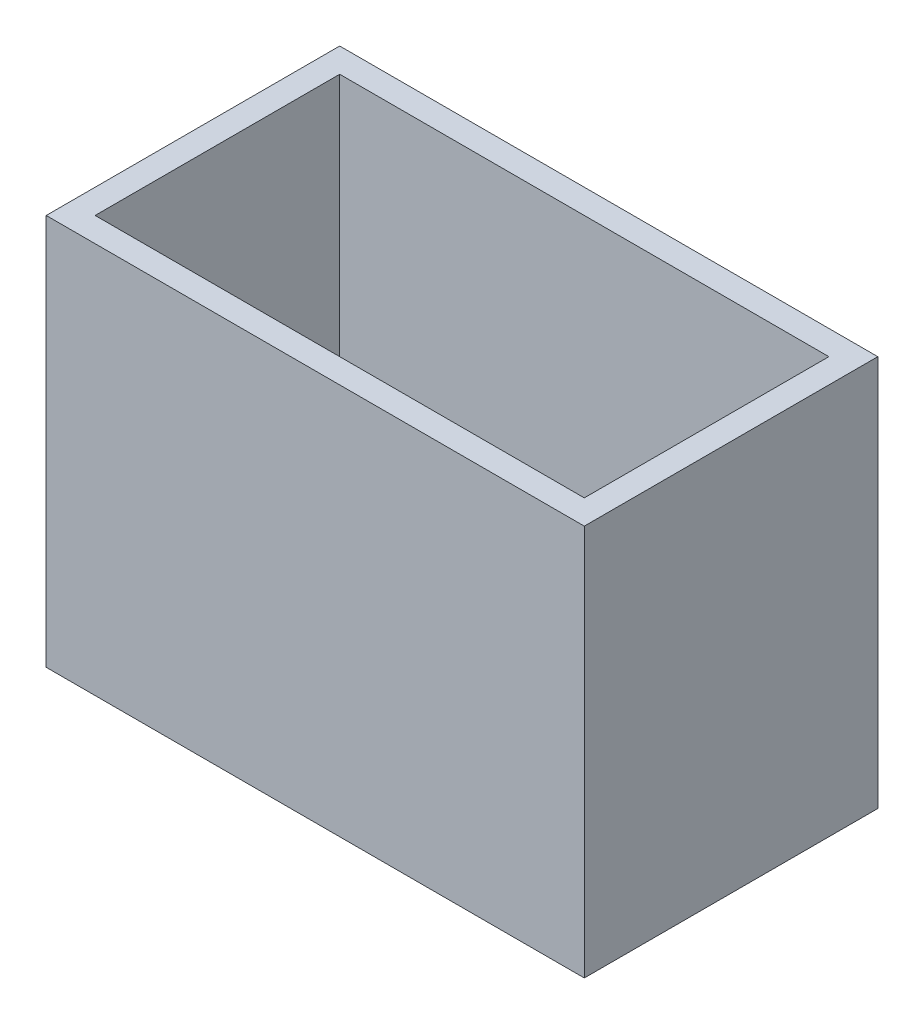
SolidWorks part; units mm, degrees
ref_plane "Front Plane" through (0, 0, 0) normal (0, 0, 1) x (1, 0, 0)
ref_plane "Top Plane" through (0, 0, 0) normal (0, 1, 0) x (1, 0, 0)
ref_plane "Right Plane" through (0, 0, 0) normal (1, 0, 0) x (0, 0, -1)
sketch "Sketch 1" plane through (0, 0, 0) normal (0, 1, 0) x (1, 0, 0)
  line L1 (-55, -30) -> (55, -30)
  line L2 (-55, -30) -> (-55, 30)
  line L3 (-55, 30) -> (55, 30)
  line L4 (55, -30) -> (55, 30)
  line L5 (-55, -30) -> (55, 30) construction
  line L6 (-55, 30) -> (55, -30) construction
  point P0 (0, 0)
  dimension "D1" = 60
  dimension "D2" = 110
extrude "Boss-Extrude1" add sketch "Sketch 1" along normal blind 80
sketch "Sketch2" plane through (0, 80, 0) normal (0, 1, 0) x (1, 0, 0)
  line L1 (-50, -25) -> (50, -25)
  line L2 (-50, -25) -> (-50, 25)
  line L3 (-50, 25) -> (50, 25)
  line L4 (50, -25) -> (50, 25)
  line L5 (-50, -25) -> (50, 25) construction
  line L6 (-50, 25) -> (50, -25) construction
  point P0 (0, 0)
  dimension "D1" = 50
  dimension "D2" = 100
extrude "Cut-Extrude1" cut sketch "Sketch2" against normal blind 75
